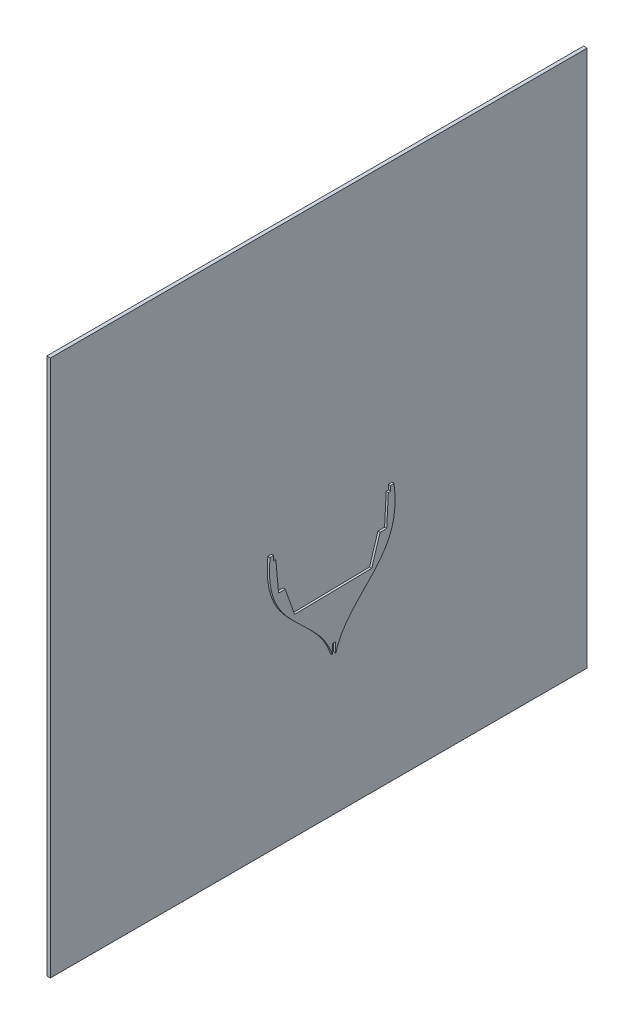
SolidWorks part; units mm, degrees
ref_plane "Plan de face" through (0, 0, 0) normal (0, 0, 1) x (1, 0, 0)
ref_plane "Plan de dessus" through (0, 0, 0) normal (0, 1, 0) x (1, 0, 0)
ref_plane "Plan de droite" through (0, 0, 0) normal (1, 0, 0) x (0, 0, -1)
sketch "Esquisse1" plane through (0, 0, 0) normal (0, 0, 1) x (1, 0, 0)
  point P0 (-20, 0)
  dimension "D1" = 20
sketch3d "Esquisse3D1"
  line L1 (-20, 1121.2893, 777.275) -> (-20, 1121.2893, -722.725)
  line L2 (-20, 1121.2893, 777.275) -> (-20, -378.7107, 777.275)
  line L3 (-20, -378.7107, 777.275) -> (-20, -378.7107, -722.725)
  line L4 (-20, 1121.2893, -722.725) -> (-20, -378.7107, -722.725)
  dimension "D1" = 1500
  dimension "D2" = 1500
extrude "Boss.-Extru.2" add sketch "Esquisse3D1" along direction (1, 0, 0) on the side of the normal blind 10 contours L2 L1 L4 L3
sketch "Esquisse4" plane through (-10, 0, 0) normal (1, 0, 0) x (0, 0, -1)
  line L0 (0, 0) -> (-7.701, 425.1082) construction
  line L1 (169.3944, 339.9131) -> (-188.5193, 333.4294) construction
  line L2 (-187.2006, 249.23) -> (169.0622, 255.6839) construction
  line L3 (-144.268, 175.2448) -> (126.4811, 180.1495) construction
sketch "Esquisse5" plane through (0, 0, 0) normal (1, 0, 0) x (0, 0, -1)
  line L0 (-7.701, 425.1082) -> (0, 0) construction
  line L2 (0, 0) -> (-0.4499, 24.8349) construction
  line L3 (-0.4499, 24.8349) -> (24.0939, 164.4281) construction
  line L4 (24.0939, 164.4281) -> (195.9789, 139.9472) construction
  line L5 (195.9789, 139.9472) -> (166.8557, 353.9524) construction
  line L8 (166.8557, 353.9524) -> (156.8557, 353.7712)
  line L9 (156.8557, 353.7712) -> (157.7232, 339.7017)
  line L10 (169.3944, 339.9131) -> (-188.5193, 333.4294) construction
  line L11 (157.7232, 339.7017) -> (151.0185, 339.5802)
  line L12 (151.0185, 339.5802) -> (146.473, 255.2747)
  line L13 (-187.2006, 249.23) -> (169.0622, 255.6839) construction
  line L14 (146.473, 255.2747) -> (127.9947, 254.9399)
  line L15 (127.9947, 254.9399) -> (104.4283, 179.75)
  line L16 (-144.268, 175.2448) -> (126.4811, 180.1495) construction
  line L17 (104.4283, 179.75) -> (-110.8701, 175.8498)
  line L18 (0, 0) -> (-0.4499, 24.8349) construction
  line L19 (-0.4499, 24.8349) -> (-30.0335, 163.4476) construction
  line L20 (-30.0335, 163.4476) -> (-200.9191, 132.7573) construction
  line L21 (-200.9191, 132.7573) -> (-179.5659, 347.6768) construction
  line L22 (-137.1444, 250.1368) -> (-110.8701, 175.8498)
  line L23 (-155.6226, 249.8021) -> (-137.1444, 250.1368)
  line L24 (-163.2186, 333.8877) -> (-155.6226, 249.8021)
  line L25 (-169.9233, 333.7663) -> (-163.2186, 333.8877)
  line L26 (-169.5659, 347.858) -> (-169.9233, 333.7663)
  line L27 (-179.5659, 347.6768) -> (-169.5659, 347.858)
  spline S0 degree 4 poles (0, 0) (-0.4499, 24.8349) (24.0939, 164.4281) (195.9789, 139.9472) (166.8557, 353.9524) knots 0 0 0 0 0 1 1 1 1 1
  spline S1 degree 4 poles (0, 0) (-0.4499, 24.8349) (-30.0335, 163.4476) (-200.9191, 132.7573) (-179.5659, 347.6768) knots 0 0 0 0 0 1 1 1 1 1
  point P30 (-3.2209, 177.7999)
  dimension "D1" = 10
extrude "Boss.-Extru.3" add sketch "Esquisse5" along normal blind 6 separate body
sketch "Esquisse6" plane through (6, 0, 0) normal (1, 0, 0) x (0, 0, -1)
  line L0 (-4.957, 25.1445) -> (-5.4461, 52.1445)
  line L1 (-5.4461, 52.1445) -> (3.5539, 52.3075)
  line L2 (3.5539, 52.3075) -> (4.043, 25.3075)
  line L3 (4.043, 25.3075) -> (117.0633, -47.527)
  line L4 (117.0633, -47.527) -> (-85.2277, -65.22)
  line L5 (-85.2277, -65.22) -> (-4.957, 25.1445)
  line L6 (-4.957, 25.1445) -> (4.043, 25.3075) construction
  line L7 (-144.268, 175.2448) -> (126.4811, 180.1495) construction
  spline S0 degree 4 poles (-179.5659, 347.6768) (-200.9191, 132.7573) (-30.0335, 163.4476) (-0.4499, 24.8349) (0, 0) knots 0 0 0 0 0 1 1 1 1 1 construction
  spline S1 degree 4 poles (0, 0) (-0.4499, 24.8349) (24.0939, 164.4281) (195.9789, 139.9472) (166.8557, 353.9524) knots 0 0 0 0 0 1 1 1 1 1 construction
  dimension "D1" = 9
  dimension "D2" = 27
extrude "Enlèv. mat.-Extru.1" cut sketch "Esquisse6" against normal blind 6
